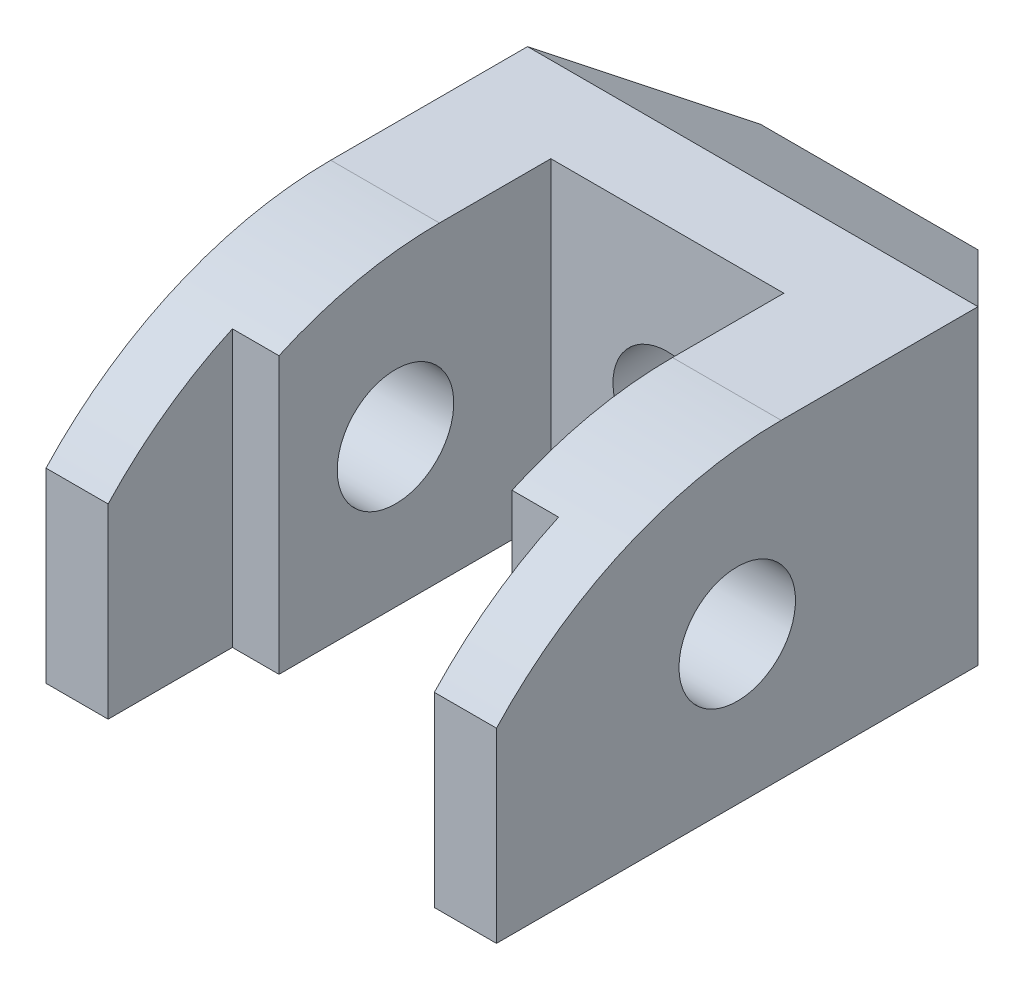
SolidWorks part; units mm, degrees
material "1060 Alloy"
ref_plane "Front Plane" through (0, 0, 0) normal (0, 0, 1) x (1, 0, 0)
ref_plane "Top Plane" through (0, 0, 0) normal (0, 1, 0) x (1, 0, 0)
ref_plane "Right Plane" through (0, 0, 0) normal (1, 0, 0) x (0, 0, -1)
sketch "Sketch1" plane through (0, 0, 0) normal (1, 0, 0) x (0, 0, -1)
  line L0 (0, 0) -> (0, 22637.3905) construction
  line L1 (1.3894, 0) -> (-22636.0011, 0) construction
  line L2 (-31, 5) -> (-31, -19)
  line L3 (-31, -19) -> (31, -19)
  line L4 (31, -19) -> (46, -10.3397)
  line L5 (46, -10.3397) -> (46, 12.3397)
  line L6 (46, 12.3397) -> (31, 21)
  line L7 (31, 21) -> (5.6606, 21)
  arc A0 (5.6606, 21) -> (-31, 5) centre (5.6606, -29) ccw
  circle A1 centre (0, 0) radius 7.5
  dimension "D7" = 15
  dimension "D11" = 50
  dimension "D2" = 40
  dimension "D3" = 30
  dimension "D4" = 30
  dimension "D5" = 15
  dimension "D6" = 15
  dimension "D8" = 31
  dimension "D9" = 19
  dimension "D10" = 24
  dimension "D12" = 62
extrude "Boss-Extrude1" add sketch "Sketch1" along normal mid plane 58
sketch "Sketch2" plane through (0, 21, 0) normal (0, 1, 0) x (1, 0, 0)
  line L0 (-29, 31) -> (-29, 56.131) construction
  line L1 (29, 31) -> (29, 54.4301) construction
  line L2 (-29, 31) -> (-14, 46)
  line L3 (29, 46) -> (-29, 46) construction
  line L4 (-14, 46) -> (-29, 46)
  line L5 (-29, 46) -> (-29, 31)
  line L6 (29, 31) -> (29, 46)
  line L7 (29, 46) -> (14, 46)
  line L8 (14, 46) -> (29, 31)
  dimension "D1" = 45
  dimension "D2" = 45
extrude "Cut-Extrude1" cut sketch "Sketch2" against normal through all
sketch "Sketch3" plane through (0, 0, -46) normal (0, 0, -1) x (-1, 0, 0)
  circle A0 centre (0, 0) radius 7
  dimension "D1" = 14
extrude "Cut-Extrude2" cut sketch "Sketch3" against normal through all
sketch "Sketch4" plane through (0, 21, 0) normal (0, 1, 0) x (1, 0, 0)
  line L0 (0, 0) -> (50000, 0) construction
  line L1 (0, 0) -> (0, 50000) construction
  line L2 (-21, -31) -> (21, -31)
  line L3 (-4.899, -31) -> (-29, -31) construction
  line L4 (-21, -31) -> (-21, -15)
  line L5 (-21, -15) -> (-15, -15)
  line L6 (-15, -15) -> (-15, 20)
  line L7 (-15, 20) -> (15, 20)
  line L8 (15, 20) -> (15, -15)
  line L9 (15, -15) -> (21, -15)
  line L10 (21, -15) -> (21, -31)
  line L11 (29, -31) -> (4.899, -31) construction
  line L12 (29, 31) -> (-29, 31) construction
  line L14 (29, -31) -> (29, 5.6606) construction
  line L15 (-29, 5.6606) -> (-29, -31) construction
  dimension "D1" = 11
  dimension "D2" = 16
  dimension "D3" = 8
  dimension "D4" = 6
  dimension "D5" = 8
extrude "Cut-Extrude3" cut sketch "Sketch4" against normal through all
equation "\"A\"= 58"
equation "\"B\"= 40"
equation "\"C\"= 62"
equation "\"D2@Sketch1\"=\"B\""
equation "\"D1@Boss-Extrude1\"=\"A\""
equation "\"D12@Sketch1\"=\"C\""
